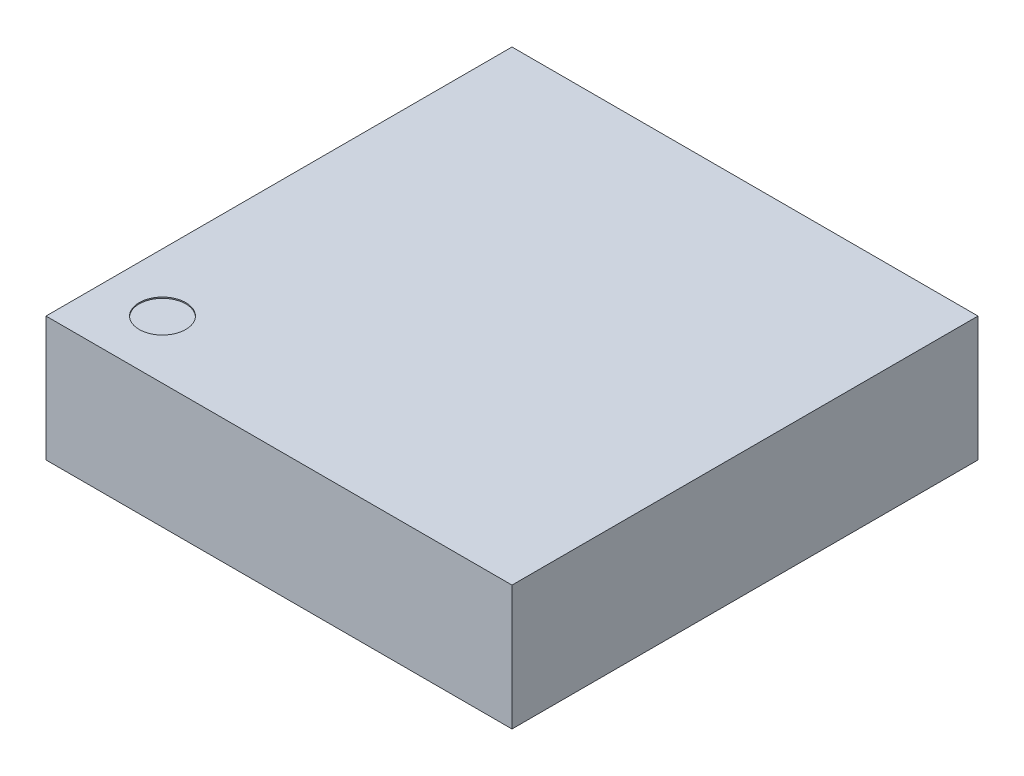
SolidWorks part; units mm, degrees
ref_plane "Front Plane" through (0, 0, 0) normal (0, 0, 1) x (1, 0, 0)
ref_plane "Top Plane" through (0, 0, 0) normal (0, 1, 0) x (1, 0, 0)
ref_plane "Right Plane" through (0, 0, 0) normal (1, 0, 0) x (0, 0, -1)
sketch "Sketch1" plane through (0, 0, 0) normal (0, 1, 0) x (1, 0, 0)
  line L0 (-1.925, 0.85) -> (-1.575, 0.85)
  line L1 (-1.925, 1.35) -> (-1.575, 1.35)
  line L2 (-1.925, 1.35) -> (-1.925, 1.15)
  line L3 (-1.925, 1.15) -> (-1.575, 1.15)
  line L4 (-1.575, 1.35) -> (-1.575, 1.15)
  line L5 (-1.925, 0.85) -> (-1.925, 0.65)
  line L6 (-1.925, 0.65) -> (-1.575, 0.65)
  line L7 (-1.575, 0.85) -> (-1.575, 0.65)
  line L8 (-1.925, 0.35) -> (-1.575, 0.35)
  line L9 (-1.925, 0.35) -> (-1.925, 0.15)
  line L10 (-1.925, 0.15) -> (-1.575, 0.15)
  line L11 (-1.575, 0.35) -> (-1.575, 0.15)
  line L12 (-0.85, 1.925) -> (-0.65, 1.925)
  line L13 (-1.35, 1.925) -> (-1.15, 1.925)
  line L14 (-1.35, 1.925) -> (-1.35, 1.575)
  line L15 (-1.35, 1.575) -> (-1.15, 1.575)
  line L16 (-1.15, 1.925) -> (-1.15, 1.575)
  line L17 (-0.85, 1.925) -> (-0.85, 1.575)
  line L18 (-0.85, 1.575) -> (-0.65, 1.575)
  line L19 (-0.65, 1.925) -> (-0.65, 1.575)
  line L20 (-0.35, 1.925) -> (-0.15, 1.925)
  line L21 (-0.35, 1.925) -> (-0.35, 1.575)
  line L22 (-0.35, 1.575) -> (-0.15, 1.575)
  line L23 (-0.15, 1.925) -> (-0.15, 1.575)
  line L24 (0, 2.1239) -> (0, -1.4493) construction
  line L25 (-2.1576, 0) -> (2.3804, 0) construction
  line L26 (0.15, 1.925) -> (0.15, 1.575)
  line L27 (0.35, 1.575) -> (0.15, 1.575)
  line L28 (0.35, 1.925) -> (0.35, 1.575)
  line L29 (0.35, 1.925) -> (0.15, 1.925)
  line L30 (0.65, 1.925) -> (0.65, 1.575)
  line L31 (0.85, 1.575) -> (0.65, 1.575)
  line L32 (0.85, 1.925) -> (0.85, 1.575)
  line L33 (1.15, 1.925) -> (1.15, 1.575)
  line L34 (1.35, 1.575) -> (1.15, 1.575)
  line L35 (1.35, 1.925) -> (1.35, 1.575)
  line L36 (1.35, 1.925) -> (1.15, 1.925)
  line L37 (0.85, 1.925) -> (0.65, 1.925)
  line L38 (1.575, 0.35) -> (1.575, 0.15)
  line L39 (1.925, 0.15) -> (1.575, 0.15)
  line L40 (1.925, 0.35) -> (1.925, 0.15)
  line L41 (1.925, 0.35) -> (1.575, 0.35)
  line L42 (1.575, 0.85) -> (1.575, 0.65)
  line L43 (1.925, 0.65) -> (1.575, 0.65)
  line L44 (1.925, 0.85) -> (1.925, 0.65)
  line L45 (1.575, 1.35) -> (1.575, 1.15)
  line L46 (1.925, 1.15) -> (1.575, 1.15)
  line L47 (1.925, 1.35) -> (1.925, 1.15)
  line L48 (1.925, 1.35) -> (1.575, 1.35)
  line L49 (1.925, 0.85) -> (1.575, 0.85)
  line L50 (1.925, -0.85) -> (1.575, -0.85)
  line L51 (1.925, -1.35) -> (1.575, -1.35)
  line L52 (1.925, -1.35) -> (1.925, -1.15)
  line L53 (1.925, -1.15) -> (1.575, -1.15)
  line L54 (1.575, -1.35) -> (1.575, -1.15)
  line L55 (1.925, -0.85) -> (1.925, -0.65)
  line L56 (1.925, -0.65) -> (1.575, -0.65)
  line L57 (1.575, -0.85) -> (1.575, -0.65)
  line L58 (1.925, -0.35) -> (1.575, -0.35)
  line L59 (1.925, -0.35) -> (1.925, -0.15)
  line L60 (1.925, -0.15) -> (1.575, -0.15)
  line L61 (1.575, -0.35) -> (1.575, -0.15)
  line L62 (0.85, -1.925) -> (0.65, -1.925)
  line L63 (1.35, -1.925) -> (1.15, -1.925)
  line L64 (1.35, -1.925) -> (1.35, -1.575)
  line L65 (1.35, -1.575) -> (1.15, -1.575)
  line L66 (1.15, -1.925) -> (1.15, -1.575)
  line L67 (0.85, -1.925) -> (0.85, -1.575)
  line L68 (0.85, -1.575) -> (0.65, -1.575)
  line L69 (0.65, -1.925) -> (0.65, -1.575)
  line L70 (0.35, -1.925) -> (0.15, -1.925)
  line L71 (0.35, -1.925) -> (0.35, -1.575)
  line L72 (0.35, -1.575) -> (0.15, -1.575)
  line L73 (0.15, -1.925) -> (0.15, -1.575)
  line L74 (-0.15, -1.925) -> (-0.15, -1.575)
  line L75 (-0.35, -1.575) -> (-0.15, -1.575)
  line L76 (-0.35, -1.925) -> (-0.35, -1.575)
  line L77 (-0.35, -1.925) -> (-0.15, -1.925)
  line L78 (-0.65, -1.925) -> (-0.65, -1.575)
  line L79 (-0.85, -1.575) -> (-0.65, -1.575)
  line L80 (-0.85, -1.925) -> (-0.85, -1.575)
  line L81 (-1.15, -1.925) -> (-1.15, -1.575)
  line L82 (-1.35, -1.575) -> (-1.15, -1.575)
  line L83 (-1.35, -1.925) -> (-1.35, -1.575)
  line L84 (-1.35, -1.925) -> (-1.15, -1.925)
  line L85 (-0.85, -1.925) -> (-0.65, -1.925)
  line L86 (-1.575, -0.35) -> (-1.575, -0.15)
  line L87 (-1.925, -0.15) -> (-1.575, -0.15)
  line L88 (-1.925, -0.35) -> (-1.925, -0.15)
  line L89 (-1.925, -0.35) -> (-1.575, -0.35)
  line L90 (-1.575, -0.85) -> (-1.575, -0.65)
  line L91 (-1.925, -0.65) -> (-1.575, -0.65)
  line L92 (-1.925, -0.85) -> (-1.925, -0.65)
  line L93 (-1.575, -1.35) -> (-1.575, -1.15)
  line L94 (-1.925, -1.15) -> (-1.575, -1.15)
  line L95 (-1.925, -1.35) -> (-1.925, -1.15)
  line L96 (-1.925, -1.35) -> (-1.575, -1.35)
  line L97 (-1.925, -0.85) -> (-1.575, -0.85)
  point P5 (-1.25, 0.25)
  point P6 (-1.25, 0.75)
  dimension "D1" = 3
extrude "Boss-Extrude1" add sketch "Sketch1" along normal blind 0.2
sketch "Sketch2" plane through (0, 0, 0) normal (0, 1, 0) x (1, 0, 0)
  line L1 (-2, 2) -> (2, 2)
  line L2 (-2, 2) -> (-2, -2)
  line L3 (-2, -2) -> (2, -2)
  line L4 (2, 2) -> (2, -2)
extrude "Boss-Extrude2" add sketch "Sketch2" along normal blind 1.07 from offset 0.01 separate body
sketch "Sketch3" plane through (0, 1.08, 0) normal (0, 1, 0) x (1, 0, 0)
  circle A0 centre (-1.5, -1.5) radius 0.2
extrude "Cut-Extrude2" cut sketch "Sketch3" against normal blind 0.01
equation "\"0.01mm.\"=1.07"
